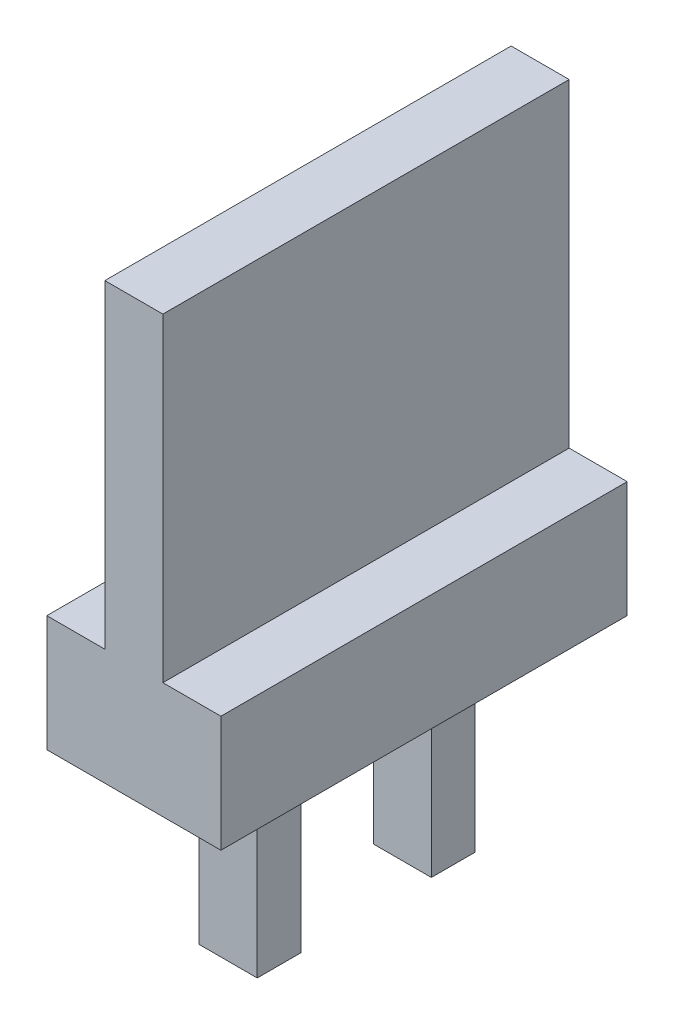
SolidWorks part; units mm, degrees
ref_plane "Front Plane" through (0, 0, 0) normal (0, 0, 1) x (1, 0, 0)
ref_plane "Top Plane" through (0, 0, 0) normal (0, 1, 0) x (1, 0, 0)
ref_plane "Right Plane" through (0, 0, 0) normal (1, 0, 0) x (0, 0, -1)
sketch "Sketch1" plane through (0, 0, 0) normal (0, 0, 1) x (1, 0, 0)
  line L0 (-2.2086, 1.7347) -> (-2.2086, 23.7347)
  line L1 (-2.2086, 23.7347) -> (1.7914, 23.7347)
  line L2 (1.7914, 23.7347) -> (1.7914, 1.7347)
  line L3 (1.7914, 1.7347) -> (5.7914, 1.7347)
  line L4 (5.7914, 1.7347) -> (5.7914, -6.2653)
  line L5 (5.7914, -6.2653) -> (-6.2086, -6.2653)
  line L6 (-6.2086, -6.2653) -> (-6.2086, 1.7347)
  line L7 (-6.2086, 1.7347) -> (-2.2086, 1.7347)
  dimension "D1" = 12
  dimension "D2" = 4
  dimension "D3" = 4
  dimension "D4" = 22
  dimension "D5" = 22
  dimension "D6" = 8
extrude "Boss-Extrude1" add sketch "Sketch1" along normal blind 28
sketch "Sketch2" plane through (0, -6.2653, 0) normal (0, -1, 0) x (1, 0, 0)
  line L6 (-4.2086, 21.5) -> (-4.2086, 6.5)
  line L7 (-4.2086, 6.5) -> (3.7914, 6.5)
  line L8 (3.7914, 6.5) -> (3.7914, 21.5)
  line L9 (3.7914, 21.5) -> (-4.2086, 21.5)
  dimension "D1" = 15
  dimension "D2" = 8
  dimension "D3" = 2
  dimension "D4" = 6.5
extrude "Boss-Extrude2" add sketch "Sketch2" along normal blind 2
sketch "Sketch3" plane through (0, 0, 21.5) normal (0, 0, 1) x (1, 0, 0)
  line L0 (-2.2061, -8.2653) -> (-2.2061, -19.1393)
  line L1 (3.7914, -8.2653) -> (-4.2086, -8.2653) construction
  line L2 (-2.2061, -19.1393) -> (1.7939, -19.1393)
  line L3 (1.7939, -19.1393) -> (1.7939, -8.2653)
  line L4 (1.7939, -8.2653) -> (-2.2061, -8.2653)
  dimension "D1" = 4
extrude "Boss-Extrude3" add sketch "Sketch3" against normal blind 3
sketch "Sketch5" plane through (0, 0, 6.5) normal (0, 0, -1) x (-1, 0, 0)
  line L0 (-1.7939, -8.2653) -> (-1.7939, -19.1393)
  line L1 (-1.7939, -19.1393) -> (2.2061, -19.1393)
  line L2 (2.2061, -19.1393) -> (2.2061, -8.2653)
  line L3 (2.2061, -8.2653) -> (-1.7939, -8.2653)
extrude "Boss-Extrude4" add sketch "Sketch5" against normal blind 3 separate body
